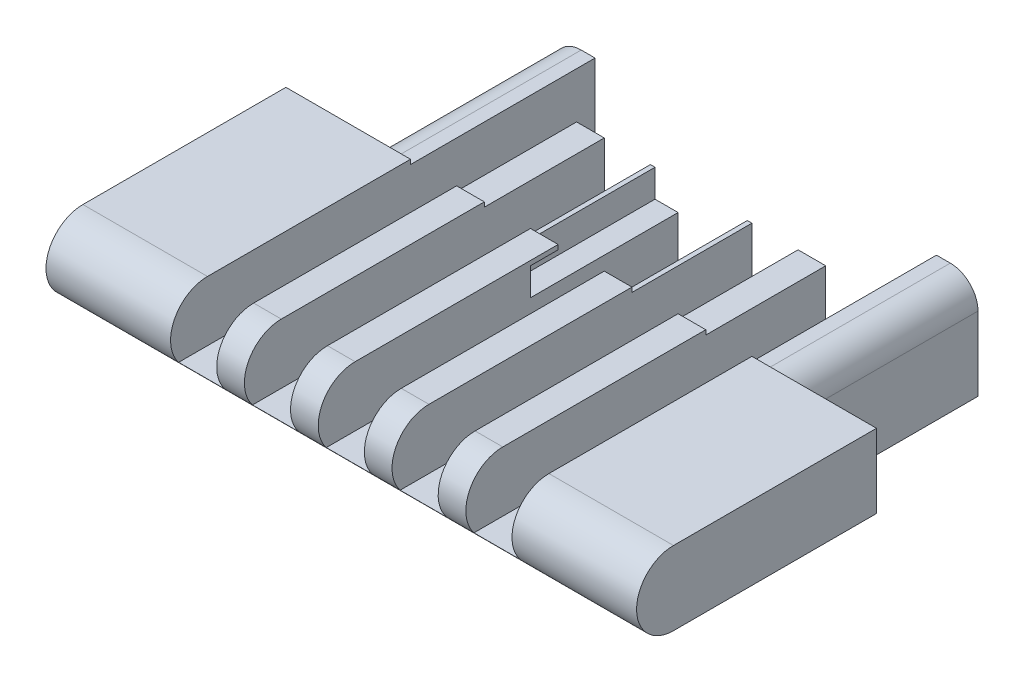
SolidWorks part; units mm, degrees
material "ABS"
ref_plane "Front Plane" through (0, 0, 0) normal (0, 0, 1) x (1, 0, 0)
ref_plane "Top Plane" through (0, 0, 0) normal (0, 1, 0) x (1, 0, 0)
ref_plane "Right Plane" through (0, 0, 0) normal (1, 0, 0) x (0, 0, -1)
sketch "Sketch1" plane through (0, 0, 0) normal (0, 0, 1) x (1, 0, 0)
  line L0 (2.5025, 0) -> (-2.5025, 0) construction
  line L1 (-2.7, 1.5) -> (2.7, 1.5)
  line L2 (-3, 1.2) -> (-3, 0)
  line L3 (-3, 0) -> (3, 0)
  line L4 (3, 1.2) -> (3, 0)
  arc A0 (-3, 1.2) -> (-2.7, 1.5) centre (-2.7, 1.2) cw
  arc A1 (3, 1.2) -> (2.7, 1.5) centre (2.7, 1.2) ccw
  point P9 (-3, 1.5)
  point P12 (3, 1.5)
  dimension "D3" = 0.3
  dimension "D1" = 1.5
  dimension "D2" = 6
extrude "Boss-Extrude1" add sketch "Sketch1" along normal blind 2
sketch "Sketch2" plane through (0, 0, 0) normal (1, 0, 0) x (0, 0, -1)
  line L0 (0, 2.25) -> (-4.2, 2.25)
  line L1 (0, 0.9075) -> (0, -0.9075) construction
  line L2 (2.035, 0) -> (-2.035, 0) construction
  line L3 (0, 1.45) -> (-4.2, 1.45)
  line L4 (0, 2.25) -> (0, 1.45)
  arc A0 (-4.2, 2.25) -> (-4.2, 1.45) centre (-4.2, 1.85) ccw
  dimension "D1" = 0.8
  dimension "D2" = 1.45
  dimension "D3" = 4.2
extrude "Boss-Extrude2" add sketch "Sketch2" along normal mid plane 6.4
sketch "Sketch3" plane through (0, 0, 2) normal (0, 0, 1) x (1, 0, 0)
  line L0 (2.035, 0) -> (-2.035, 0) construction
  line L1 (-2, 2.2) -> (2, 2.2)
  line L2 (-2.3, 1.9) -> (-2.3, 1.1)
  line L3 (-1.8, 0.6) -> (1.8, 0.6)
  line L4 (2.3, 1.9) -> (2.3, 1.1)
  line L5 (0, -0.9075) -> (0, 0.9075) construction
  line L6 (-2.3, 1.1) -> (-1.8, 0.6)
  line L7 (1.8, 0.6) -> (2.3, 1.1)
  arc A0 (2, 2.2) -> (2.3, 1.9) centre (2, 1.9) cw
  arc A1 (-2, 2.2) -> (-2.3, 1.9) centre (-2, 1.9) ccw
  point P1 (2.3, 0.6)
  point P2 (-2.3, 0.6)
  point P14 (2.3, 2.2)
  dimension "D5" = 0.3
  dimension "D1" = 4.6
  dimension "D2" = 1.6
  dimension "D3" = 0.6
  dimension "D4" = 2.3
extrude "Cut-Extrude1" cut sketch "Sketch3" against normal blind 4.8 flip side to cut
sketch "Sketch4" plane through (0, 0, 0) normal (0, 0, 1) x (1, 0, 0)
  line L1 (0.5, 2.2) -> (-0.5, 2.2)
  line L2 (0.5, 2.2) -> (0.5, 1.9)
  line L3 (0.5, 1.9) -> (-0.5, 1.9)
  line L4 (-0.5, 2.2) -> (-0.5, 1.9)
  line L5 (0, -0.9075) -> (0, 0.9075) construction
  line L7 (-2, 2.2) -> (2, 2.2) construction
  dimension "D1" = 1
  dimension "D2" = 0.5
  dimension "D3" = 0.3
extrude "Cut-Extrude3" cut sketch "Sketch4" along normal blind 2.3
sketch "Sketch5" plane through (0, 0, 0) normal (0, 1, 0) x (1, 0, 0)
  line L0 (-1.87, 0) -> (1.87, 0) construction
  line L1 (-1.85, 0) -> (1.85, 0)
  line L2 (-1.85, 0) -> (-1.85, -1)
  line L3 (-1.85, -1) -> (-1.35, -1)
  line L4 (1.85, 0) -> (1.85, -1)
  line L5 (0, -1.87) -> (0, 1.87) construction
  line L6 (-1.05, -1) -> (-0.55, -1)
  line L7 (-1.35, -0.7) -> (-1.05, -0.7)
  line L8 (-1.35, -0.7) -> (-1.35, -1)
  line L9 (-0.25, -1) -> (0.25, -1)
  line L10 (-1.05, -0.7) -> (-1.05, -1)
  line L11 (-0.55, -0.7) -> (-0.25, -0.7)
  line L12 (-0.55, -0.7) -> (-0.55, -1)
  line L13 (0.55, -1) -> (1.05, -1)
  line L14 (-0.25, -0.7) -> (-0.25, -1)
  line L15 (0.25, -0.7) -> (0.55, -0.7)
  line L16 (0.25, -0.7) -> (0.25, -1)
  line L17 (1.35, -1) -> (1.85, -1)
  line L18 (0.55, -0.7) -> (0.55, -1)
  line L19 (1.05, -0.7) -> (1.35, -0.7)
  line L20 (1.05, -0.7) -> (1.05, -1)
  line L22 (1.35, -0.7) -> (1.35, -1)
  dimension "D1" = 3.7
  dimension "D2" = 1.85
  dimension "D3" = 0.3
  dimension "D4" = 0.5
  dimension "D5" = 1
extrude "Cut-Extrude6" cut sketch "Sketch5" along normal through all
sketch "Sketch6" plane through (0, 0, 2) normal (0, 0, 1) x (1, 0, 0)
  line L0 (1.85, 2.2) -> (1.85, 0.65) construction
  line L1 (1.85, 1.9) -> (1.35, 1.9)
  line L2 (1.85, 1.9) -> (1.85, 1.4)
  line L3 (1.85, 1.4) -> (1.35, 1.4)
  line L4 (1.35, 1.9) -> (1.35, 1.4)
  line L5 (1.35, 2.2) -> (1.35, 0.6) construction
  line L6 (1.05, 2.2) -> (1.05, 0.6) construction
  line L7 (1.05, 1.9) -> (0.55, 1.9)
  line L8 (1.05, 1.9) -> (1.05, 1.4)
  line L9 (1.05, 1.4) -> (0.55, 1.4)
  line L10 (0.55, 1.9) -> (0.55, 1.4)
  line L11 (0.55, 2.2) -> (0.55, 0.6) construction
  line L12 (0.25, 1.9) -> (0.25, 0.6) construction
  line L13 (0.25, 1.9) -> (-0.25, 1.9)
  line L14 (0.25, 1.9) -> (0.25, 1.4)
  line L15 (0.25, 1.4) -> (-0.25, 1.4)
  line L16 (-0.25, 1.9) -> (-0.25, 1.4)
  line L17 (-0.25, 1.9) -> (-0.25, 0.6) construction
  line L18 (-0.55, 2.2) -> (-0.55, 0.6) construction
  line L19 (-0.55, 1.9) -> (-1.05, 1.9)
  line L20 (-0.55, 1.9) -> (-0.55, 1.4)
  line L21 (-0.55, 1.4) -> (-1.05, 1.4)
  line L22 (-1.05, 1.9) -> (-1.05, 1.4)
  line L23 (-1.05, 2.2) -> (-1.05, 0.6) construction
  line L24 (-1.35, 2.2) -> (-1.35, 0.6) construction
  line L25 (-1.35, 1.9) -> (-1.85, 1.9)
  line L26 (-1.35, 1.9) -> (-1.35, 1.4)
  line L27 (-1.35, 1.4) -> (-1.85, 1.4)
  line L28 (-1.85, 1.9) -> (-1.85, 1.4)
  line L29 (-1.85, 2.2) -> (-1.85, 0.65) construction
  line L30 (2.035, 0) -> (-2.035, 0) construction
  dimension "D1" = 1.9
  dimension "D2" = 0.5
extrude "Cut-Extrude7" cut sketch "Sketch6" against normal blind 2
sketch "Sketch7" plane through (0, 0, 0) normal (0, 0, 1) x (1, 0, 0)
  line L0 (1.85, 2.2) -> (1.85, 0.65) construction
  line L1 (1.85, 2.4) -> (1.35, 2.4)
  line L2 (1.85, 2.4) -> (1.85, 1.6)
  line L3 (1.85, 1.6) -> (1.35, 1.6)
  line L4 (1.35, 2.4) -> (1.35, 1.6)
  line L5 (1.05, 2.2) -> (1.05, 0.6) construction
  line L6 (1.05, 2.4) -> (0.55, 2.4)
  line L7 (1.05, 2.4) -> (1.05, 1.6)
  line L8 (1.05, 1.6) -> (0.55, 1.6)
  line L9 (0.55, 2.4) -> (0.55, 1.6)
  line L10 (0.25, 1.9) -> (0.25, 0.6) construction
  line L11 (0.25, 2.4) -> (-0.25, 2.4)
  line L12 (0.25, 2.4) -> (0.25, 1.6)
  line L13 (0.25, 1.6) -> (-0.25, 1.6)
  line L14 (-0.25, 2.4) -> (-0.25, 1.6)
  line L16 (-0.55, 2.2) -> (-0.55, 0.6) construction
  line L17 (-0.55, 2.4) -> (-1.05, 2.4)
  line L18 (-0.55, 2.4) -> (-0.55, 1.6)
  line L19 (-0.55, 1.6) -> (-1.05, 1.6)
  line L20 (-1.05, 2.4) -> (-1.05, 1.6)
  line L21 (-1.85, 2.2) -> (-1.85, 0.65) construction
  line L22 (-1.35, 1.6) -> (-1.85, 1.6)
  line L23 (-1.35, 1.6) -> (-1.35, 2.4)
  line L24 (-1.35, 2.4) -> (-1.85, 2.4)
  line L25 (-1.85, 1.6) -> (-1.85, 2.4)
  line L26 (-1.05, 2.2) -> (-1.05, 0.6) construction
  line L29 (2.53, 0) -> (-2.53, 0) construction
  line L30 (-0.25, 1.45) -> (-0.25, 1.4) construction
  line L32 (1.35, 1.45) -> (1.35, 1.4) construction
  line L33 (0.55, 1.45) -> (0.55, 1.4) construction
  dimension "D1" = 0.8
  dimension "D2" = 1.6
extrude "Cut-Extrude8" cut sketch "Sketch7" along normal blind 7
sketch "Sketch8" plane through (0, 0.6, 0) normal (0, 1, 0) x (1, 0, 0)
  line L0 (-0.9075, 0) -> (0.9075, 0) construction
  line L1 (-3, 0) -> (3, 0)
  line L2 (-3, 0) -> (-3, -1)
  line L3 (-3, -1) -> (3, -1)
  line L4 (3, 0) -> (3, -1)
  line L6 (0, -0.9075) -> (0, 0.9075) construction
  dimension "D1" = 6
  dimension "D2" = 3
  dimension "D3" = 1
extrude "Cut-Extrude9" cut sketch "Sketch8" along normal blind 0.5
